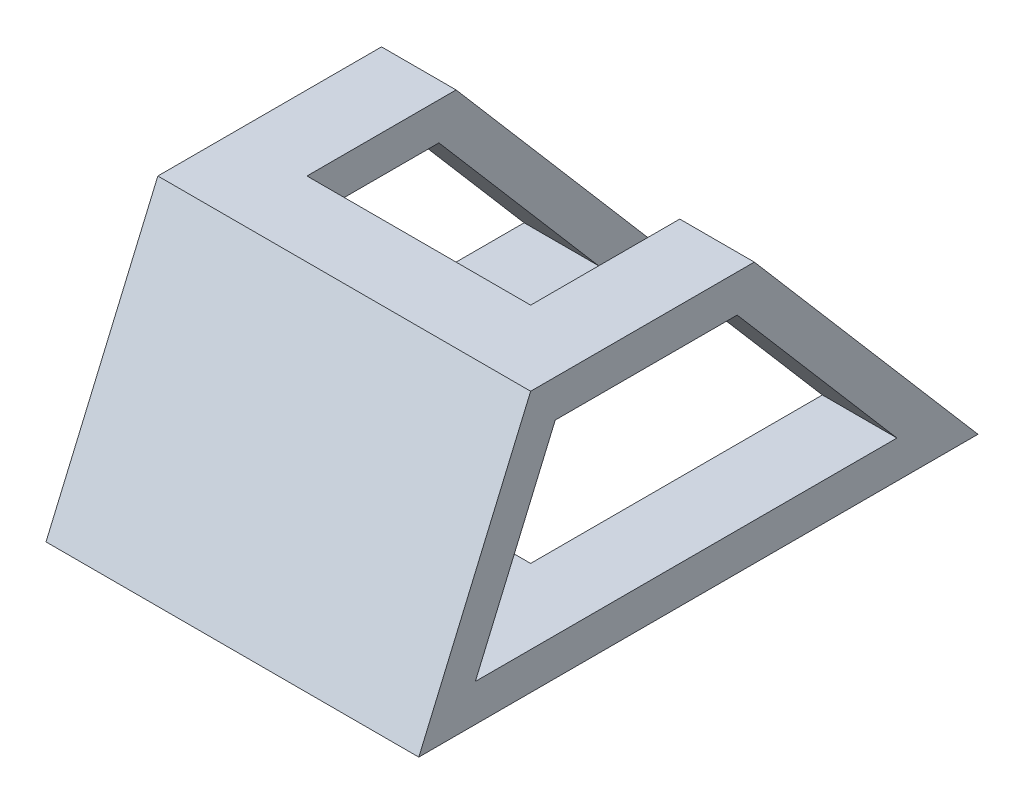
SolidWorks part; units mm, degrees
ref_plane "Front Plane" through (0, 0, 0) normal (0, 0, 1) x (1, 0, 0)
ref_plane "Top Plane" through (0, 0, 0) normal (0, 1, 0) x (1, 0, 0)
ref_plane "Right Plane" through (0, 0, 0) normal (1, 0, 0) x (0, 0, -1)
sketch "Sketch2" plane through (0, 0, 0) normal (1, 0, 0) x (0, 0, -1)
  line L0 (-53.3106, -27.6041) -> (96.6894, -27.6041)
  line L1 (96.6894, -27.6041) -> (36.6894, 42.3959)
  line L2 (36.6894, 42.3959) -> (-23.3106, 42.3959)
  line L3 (-23.3106, 42.3959) -> (-53.3106, -27.6041)
  line L4 (32.09, 32.3959) -> (-16.7167, 32.3959)
  line L5 (-16.7167, 32.3959) -> (-38.1452, -17.6041)
  line L6 (-38.1452, -17.6041) -> (74.9472, -17.6041)
  line L7 (74.9472, -17.6041) -> (32.09, 32.3959)
  dimension "D1" = 150
  dimension "D2" = 60
  dimension "D3" = 30
  dimension "D4" = 70
  dimension "D5" = 10
extrude "Boss-Extrude1" add sketch "Sketch2" against normal blind 100
sketch "Sketch4" plane through (0, 42.3959, 0) normal (0, 1, 0) x (1, 0, 0)
  line L0 (-100, 96.6894) -> (0, 96.6894) construction
  line L1 (-80, 96.6894) -> (-20, 96.6894)
  line L2 (-80, 96.6894) -> (-80, -3.3106)
  line L3 (-80, -3.3106) -> (-20, -3.3106)
  line L4 (-20, 96.6894) -> (-20, -3.3106)
  line L5 (-80, 96.6894) -> (-20, -3.3106) construction
  line L6 (-80, -3.3106) -> (-20, 96.6894) construction
  point P0 (-50, 46.6894)
  dimension "D1" = 100
  dimension "D2" = 20
  dimension "D3" = 60
extrude "Cut-Extrude1" cut sketch "Sketch4" against normal up to surface (70 mm away) up to face at (-50, -27.6041, -21.6894)
